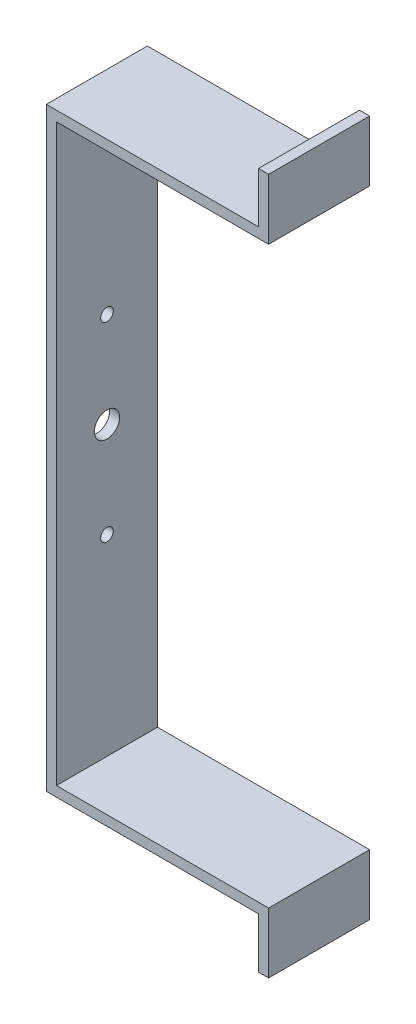
SolidWorks part; units mm, degrees
ref_plane "Front" through (0, 0, 0) normal (0, 0, 1) x (1, 0, 0)
ref_plane "Top" through (0, 0, 0) normal (0, 1, 0) x (1, 0, 0)
ref_plane "Right" through (0, 0, 0) normal (1, 0, 0) x (0, 0, -1)
sketch "Sketch1" plane through (0, 0, 0) normal (0, 0, 1) x (1, 0, 0)
  line L0 (53.34, -74.803) -> (53.34, -87.503)
  line L1 (0, 0) -> (34.0061, 0) construction
  line L2 (53.34, 74.803) -> (53.34, 87.503)
  line L21 (53.34, 74.803) -> (0, 74.803)
  line L22 (0, 74.803) -> (0, -74.803)
  line L23 (0, -74.803) -> (53.34, -74.803)
  dimension "D1" = 149.606
  dimension "D2" = 53.34
  dimension "D3" = 12.7
extrude "Base-Extrude-Thin" add sketch "Sketch1" along normal mid plane 25.4 thin thin type one direction reverse wall 2.54
sketch "Sketch2" plane through (2.54, 0, 0) normal (1, 0, 0) x (0, 0, -1)
  circle A0 centre (0, 0) radius 3.175
  dimension "D1" = 6.35
extrude "Cut-Extrude1" cut sketch "Sketch2" against normal through all
sketch "Sketch3" plane through (0, 0, 0) normal (-1, 0, 0) x (0, 0, 1)
  circle A0 centre (0, 23.9776) radius 1.5875 construction
  circle A1 centre (0, 23.9776) radius 1.5875
extrude "Cut-Extrude2" cut sketch "Sketch3" against normal through all
sketch "Sketch4" plane through (0, 0, 0) normal (-1, 0, 0) x (0, 0, 1)
  circle A0 centre (0, -23.9776) radius 1.5875 construction
  circle A1 centre (0, -23.9776) radius 1.5875
extrude "Cut-Extrude3" cut sketch "Sketch4" against normal through all
